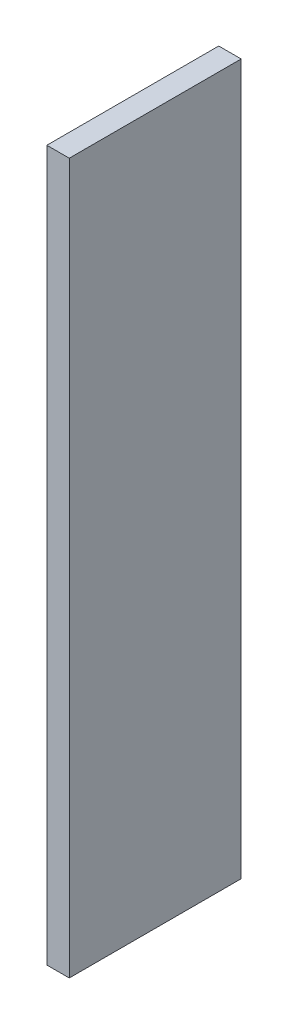
SolidWorks part; units mm, degrees
ref_plane "Front" through (0, 0, 0) normal (0, 0, 1) x (1, 0, 0)
ref_plane "Top" through (0, 0, 0) normal (0, 1, 0) x (1, 0, 0)
ref_plane "Right" through (0, 0, 0) normal (1, 0, 0) x (0, 0, -1)
sketch "Sketch1" plane through (0, 0, 0) normal (0, 1, 0) x (1, 0, 0)
  line L1 (-76.2, 584.2) -> (76.2, 584.2)
  line L2 (-76.2, 584.2) -> (-76.2, -584.2)
  line L3 (-76.2, -584.2) -> (76.2, -584.2)
  line L4 (76.2, 584.2) -> (76.2, -584.2)
  line L5 (-76.2, 584.2) -> (76.2, -584.2) construction
  line L6 (-76.2, -584.2) -> (76.2, 584.2) construction
  point P0 (0, 0)
  dimension "D1" = 152.4
  dimension "D2" = 1168.4
extrude "Boss-Extrude1" add sketch "Sketch1" along normal blind 4826
